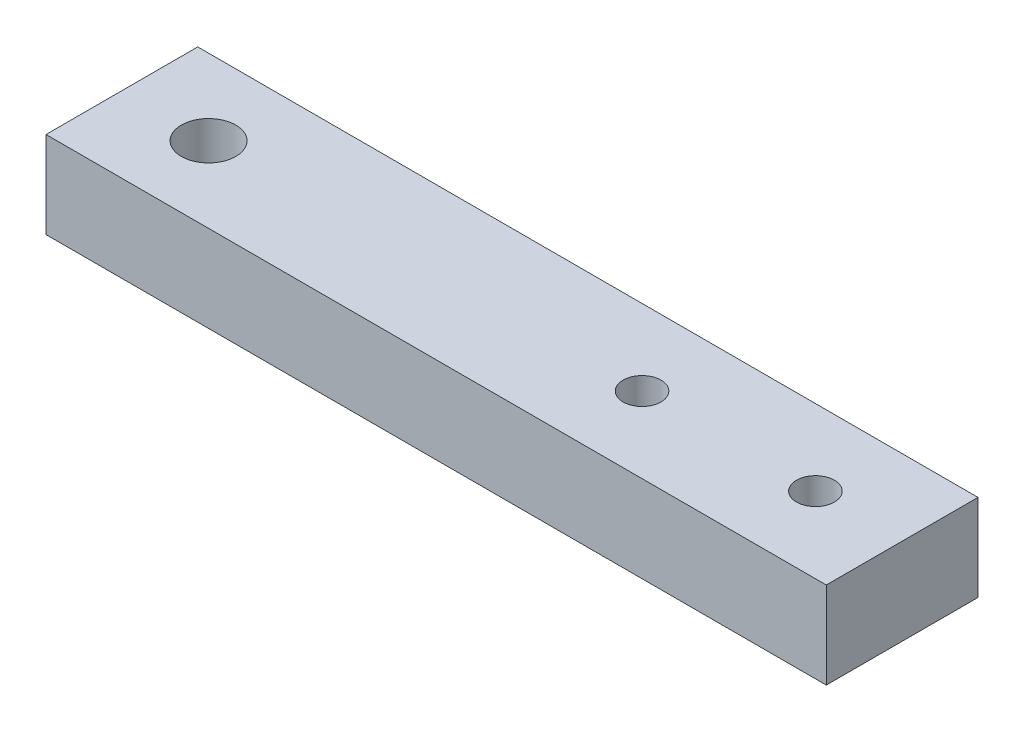
SolidWorks part; units mm, degrees
material "Beech"
ref_plane "Front Plane" through (0, 0, 0) normal (0, 0, 1) x (1, 0, 0)
ref_plane "Top Plane" through (0, 0, 0) normal (0, 1, 0) x (1, 0, 0)
ref_plane "Right Plane" through (0, 0, 0) normal (1, 0, 0) x (0, 0, -1)
sketch "Sketch1" plane through (0, 0, 0) normal (0, 1, 0) x (1, 0, 0)
  line L1 (0, 0) -> (304.8, 0)
  line L2 (0, 0) -> (0, 304.8)
  line L3 (0, 304.8) -> (304.8, 304.8)
  line L4 (304.8, 0) -> (304.8, 304.8)
  dimension "D1" = 304.8
  dimension "D2" = 304.8
extrude "Boss-Extrude1" add sketch "Sketch1" along normal blind 6.35
sketch "Sketch2" plane through (0, 6.35, 0) normal (0, 1, 0) x (1, 0, 0)
  line L1 (304.8, 304.8) -> (0, 304.8) construction
  line L2 (57.15, 304.8) -> (57.15, 293.6875)
  line L3 (57.15, 293.6875) -> (0, 293.6875)
  line L4 (0, 304.8) -> (0, 0) construction
  line L6 (0, 293.6875) -> (0, 0)
  line L7 (0, 0) -> (304.8, 0)
  line L8 (304.8, 0) -> (304.8, 304.8)
  line L9 (304.8, 304.8) -> (57.15, 304.8)
  dimension "D1" = 57.15
  dimension "D2" = 11.1125
extrude "Cut-Extrude2" cut sketch "Sketch2" against normal blind 6.35 contours L3 L6 L7 L8 L9 L2
sketch "Sketch3" plane through (0, 6.35, 0) normal (0, 1, 0) x (1, 0, 0)
  line L0 (0, 304.8) -> (0, 293.6875) construction
  line L1 (57.15, 304.8) -> (57.15, 293.6875) construction
  line L2 (57.15, 304.8) -> (0, 304.8) construction
  circle A0 centre (6.35, 299.2438) radius 1.9939
  circle A1 centre (50.8, 299.2438) radius 1.3891
  circle A2 centre (38.1, 299.2438) radius 1.3891
  dimension "D1" = 3.9878
  dimension "D2" = 6.35
  dimension "D3" = 2.7781
  dimension "D4" = 2.7781
  dimension "D5" = 6.35
  dimension "D6" = 19.05
  dimension "D7" = 5.5562
  dimension "D8" = 5.5562
  dimension "D9" = 5.5562
extrude "Cut-Extrude3" cut sketch "Sketch3" against normal through all
